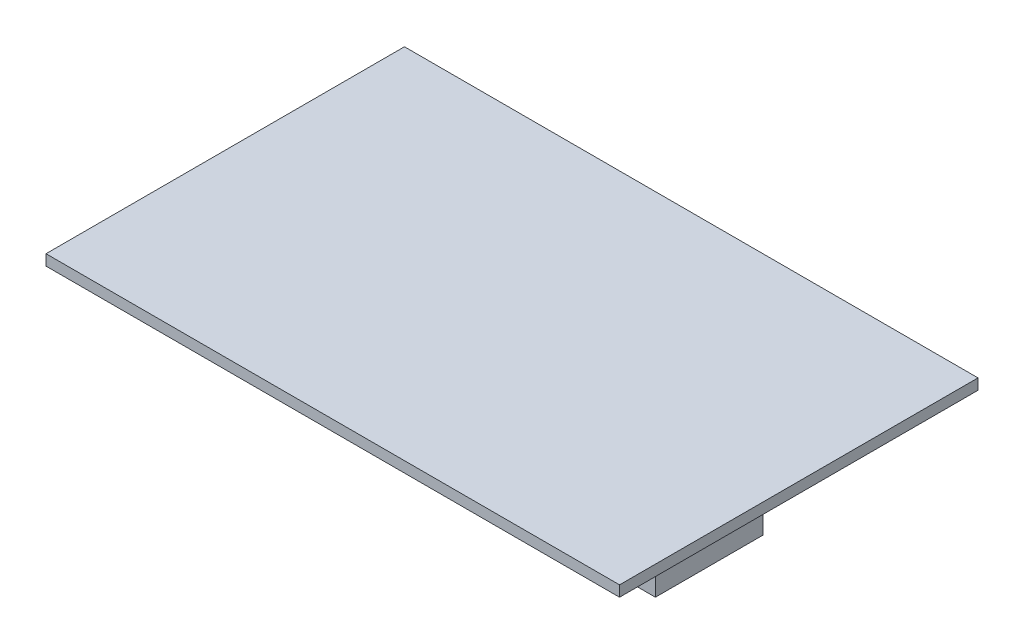
SolidWorks part; units mm, degrees
ref_plane "Front Plane" through (0, 0, 0) normal (0, 0, 1) x (1, 0, 0)
ref_plane "Top Plane" through (0, 0, 0) normal (0, 1, 0) x (1, 0, 0)
ref_plane "Right Plane" through (0, 0, 0) normal (1, 0, 0) x (0, 0, -1)
sketch "Sketch1" plane through (0, 0, 0) normal (0, 1, 0) x (1, 0, 0)
  line L1 (-80, -50) -> (80, -50)
  line L2 (-80, -50) -> (-80, 50)
  line L3 (-80, 50) -> (80, 50)
  line L4 (80, -50) -> (80, 50)
  line L5 (-80, -50) -> (80, 50) construction
  line L6 (-80, 50) -> (80, -50) construction
  point P0 (0, 0)
  dimension "D1" = 100
  dimension "D2" = 160
extrude "Boss-Extrude1" add sketch "Sketch1" along normal blind 3
sketch "Sketch2" plane through (0, 0, 0) normal (0, 1, 0) x (1, 0, 0)
  line L1 (45, 15) -> (55, 15)
  line L2 (45, 15) -> (45, -15)
  line L3 (45, -15) -> (55, -15)
  line L4 (55, 15) -> (55, -15)
  line L5 (45, 15) -> (55, -15) construction
  line L6 (45, -15) -> (55, 15) construction
  point P0 (50, 0)
  point P5 (0, 0)
  dimension "D1" = 10
  dimension "D2" = 50
  dimension "D3" = 30
extrude "Boss-Extrude2" add sketch "Sketch2" against normal blind 30
sketch "Sketch3" plane through (45, 0, 0) normal (-1, 0, 0) x (0, 0, 1)
  circle A0 centre (0, -20) radius 18
  point P2 (0, 0)
  dimension "D1" = 36
  dimension "D2" = 20
extrude "Boss-Extrude3" add sketch "Sketch3" along normal blind 80
